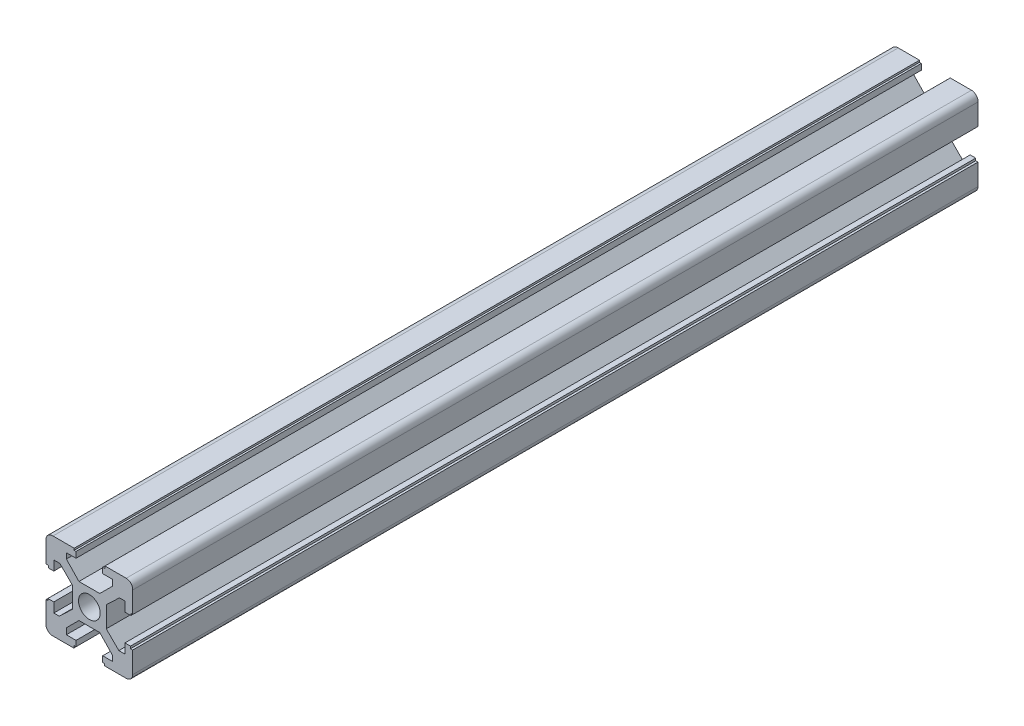
SolidWorks part; units mm, degrees
ref_plane "Front Plane" through (0, 0, 0) normal (0, 0, 1) x (1, 0, 0)
ref_plane "Top Plane" through (0, 0, 0) normal (0, 1, 0) x (1, 0, 0)
ref_plane "Right Plane" through (0, 0, 0) normal (1, 0, 0) x (0, 0, -1)
sketch "Sketch1" plane through (0, 0, 0) normal (0, 0, 1) x (1, 0, 0)
  line L0 (9.5731, 3.4975) -> (10, 3.4975)
  line L1 (9.5658, 3.075) -> (9.5731, 3.4975)
  line L2 (8.2, 3.075) -> (9.5658, 3.075)
  line L3 (8.2, 5.3047) -> (8.2, 3.075)
  line L4 (8.2, 5.3047) -> (6.9404, 5.3047)
  line L5 (-10, -3.4975) -> (-10, -8.3975)
  line L6 (-8.5, -10) -> (-3.6, -10)
  line L7 (3.9, 2.4047) -> (6.9404, 5.3047)
  line L8 (9.4791, -3.6) -> (10, -3.6)
  line L9 (9.4791, -3.075) -> (9.4791, -3.6)
  line L10 (8.2, -3.075) -> (9.4791, -3.075)
  line L11 (8.2, -5.3047) -> (8.2, -3.075)
  line L12 (8.2, -5.3047) -> (6.8, -5.3047)
  line L13 (3.9, -2.4047) -> (6.8, -5.3047)
  line L14 (3.9, -2.4047) -> (3.9, 2.4047)
  line L15 (3.4975, -9.5731) -> (3.4975, -10)
  line L16 (3.075, -9.5658) -> (3.4975, -9.5731)
  line L17 (3.075, -8.2) -> (3.075, -9.5658)
  line L18 (5.3047, -8.2) -> (3.075, -8.2)
  line L19 (5.3047, -8.2) -> (5.3047, -6.9404)
  line L20 (3.4975, -10) -> (8.3975, -10)
  line L21 (10, -8.5) -> (10, -3.6)
  line L22 (2.4047, -3.9) -> (5.3047, -6.9404)
  line L23 (-3.6, -9.4791) -> (-3.6, -10)
  line L24 (-3.075, -9.4791) -> (-3.6, -9.4791)
  line L25 (-3.075, -8.2) -> (-3.075, -9.4791)
  line L26 (-5.3047, -8.2) -> (-3.075, -8.2)
  line L27 (-5.3047, -8.2) -> (-5.3047, -6.8)
  line L28 (-2.4047, -3.9) -> (-5.3047, -6.8)
  line L29 (-2.4047, -3.9) -> (2.4047, -3.9)
  line L30 (-9.5731, -3.4975) -> (-10, -3.4975)
  line L31 (-9.5658, -3.075) -> (-9.5731, -3.4975)
  line L32 (-8.2, -3.075) -> (-9.5658, -3.075)
  line L33 (-8.2, -5.3047) -> (-8.2, -3.075)
  line L34 (-8.2, -5.3047) -> (-6.9404, -5.3047)
  line L35 (10, 3.4975) -> (10, 8.3975)
  line L36 (8.5, 10) -> (3.6, 10)
  line L37 (-3.9, -2.4047) -> (-6.9404, -5.3047)
  line L38 (-9.4791, 3.6) -> (-10, 3.6)
  line L39 (-9.4791, 3.075) -> (-9.4791, 3.6)
  line L40 (-8.2, 3.075) -> (-9.4791, 3.075)
  line L41 (-8.2, 5.3047) -> (-8.2, 3.075)
  line L42 (-8.2, 5.3047) -> (-6.8, 5.3047)
  line L43 (-3.9, 2.4047) -> (-6.8, 5.3047)
  line L44 (-3.9, 2.4047) -> (-3.9, -2.4047)
  line L45 (-2.4047, 3.9) -> (-5.3047, 6.9404)
  line L47 (-5.3047, 8.2) -> (-5.3047, 6.9404)
  line L48 (2.4047, 3.9) -> (5.3047, 6.8)
  line L49 (5.3047, 8.2) -> (5.3047, 6.8)
  line L50 (-3.4975, 10) -> (-8.3975, 10)
  line L51 (-10, 8.5) -> (-10, 3.6)
  line L52 (-10, -10) -> (10, -10) construction
  line L53 (-10, -10) -> (-10, 10) construction
  line L54 (-10, 10) -> (10, 10) construction
  line L55 (10, -10) -> (10, 10) construction
  line L56 (-10, -10) -> (10, 10) construction
  line L57 (-10, 10) -> (10, -10) construction
  line L61 (0, 0) -> (-3.9, 0) construction
  line L62 (0, 0) -> (0, 3.9) construction
  line L63 (0, 0) -> (3.9, 0) construction
  line L64 (-3, 6.4) -> (3, 6.4) construction
  line L65 (-3, 6.4) -> (-3, 4.9) construction
  line L66 (-3, 4.9) -> (3, 4.9) construction
  line L67 (3.6, 9.4791) -> (3.6, 10)
  line L68 (3.075, 9.4791) -> (3.6, 9.4791)
  line L69 (3.075, 8.2) -> (3.075, 9.4791)
  line L70 (0, 0) -> (0, -3.9) construction
  line L71 (5.3047, 8.2) -> (3.075, 8.2)
  line L77 (3, 6.4) -> (3, 4.9) construction
  line L78 (-3, 6.4) -> (3, 4.9) construction
  line L79 (-3, 4.9) -> (3, 6.4) construction
  line L87 (2.4047, 3.9) -> (-2.4047, 3.9)
  line L89 (-5.3047, 8.2) -> (-3.075, 8.2)
  line L90 (-3.075, 8.2) -> (-3.075, 9.5658)
  line L91 (-3.075, 9.5658) -> (-3.4975, 9.5731)
  line L92 (-3.4975, 9.5731) -> (-3.4975, 10)
  circle A0 centre (0, 0) radius 2.5
  arc A1 (-10, -8.3975) -> (-8.5, -10) centre (-8.5035, -8.5) ccw
  arc A4 (8.3975, -10) -> (10, -8.5) centre (8.5, -8.5035) ccw
  arc A7 (10, 8.3975) -> (8.5, 10) centre (8.5035, 8.5) ccw
  arc A10 (-8.3975, 10) -> (-10, 8.5) centre (-8.5, 8.5035) ccw
  point P59 (0, 0)
  point P67 (0, 0)
  dimension "D1" = 6
  dimension "D2" = 1.5
  dimension "D3" = 4
  dimension "D4" = 3.075
  dimension "D5" = 3.075
  dimension "D6" = 3.075
  dimension "D7" = 20
  dimension "D8" = 20
extrude "Boss-Extrude1" add sketch "Sketch1" along normal blind 195
